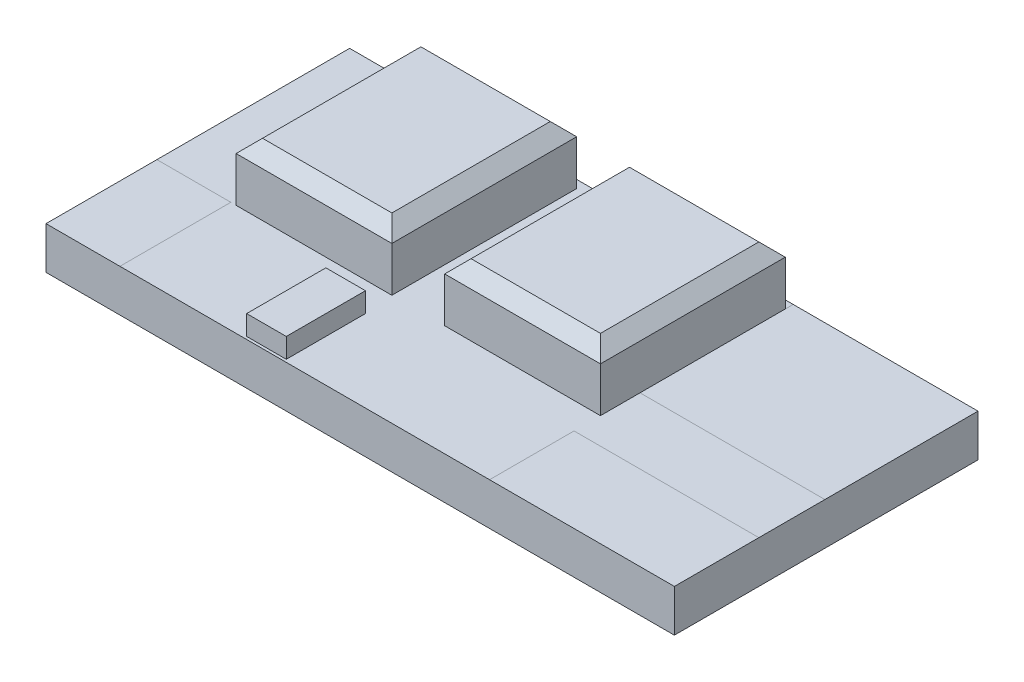
SolidWorks part; units mm, degrees
ref_plane "Alzado" through (0, 0, 0) normal (0, 0, 1) x (1, 0, 0)
ref_plane "Planta" through (0, 0, 0) normal (0, 1, 0) x (1, 0, 0)
ref_plane "Vista lateral" through (0, 0, 0) normal (1, 0, 0) x (0, 0, -1)
sketch "Croquis1" plane through (0, 0, 0) normal (0, 1, 0) x (1, 0, 0)
  line L1 (-11.9, 5.75) -> (11.9, 5.75)
  line L2 (-11.9, 5.75) -> (-11.9, -5.75)
  line L3 (-11.9, -5.75) -> (11.9, -5.75)
  line L4 (11.9, 5.75) -> (11.9, -5.75)
  line L5 (-11.9, 5.75) -> (11.9, -5.75) construction
  line L6 (-11.9, -5.75) -> (11.9, 5.75) construction
  point P0 (0, 0)
  dimension "D1" = 23.8
  dimension "D2" = 11.5
extrude "Saliente-Extruir1" add sketch "Croquis1" along normal blind 1.6
sketch "Croquis2" plane through (0, 1.6, 0) normal (0, 1, 0) x (1, 0, 0)
  line L0 (11.9, 5.75) -> (-11.9, 5.75) construction
  line L1 (-1, 5.45) -> (4.9, 5.45)
  line L2 (-1, 5.45) -> (-1, -1.55)
  line L3 (-1, -1.55) -> (4.9, -1.55)
  line L4 (4.9, 5.45) -> (4.9, -1.55)
  line L5 (-3, 5.45) -> (-8.9, 5.45)
  line L6 (-3, 5.45) -> (-3, -1.55)
  line L7 (-3, -1.55) -> (-8.9, -1.55)
  line L8 (-8.9, 5.45) -> (-8.9, -1.55)
  line L9 (-11.9, 5.75) -> (-11.9, -5.75) construction
  dimension "D1" = 5.9
  dimension "D2" = 7
  dimension "D3" = 0.3
  dimension "D4" = 2
  dimension "D5" = 3
extrude "Saliente-Extruir2" add sketch "Croquis2" along normal blind 2.2 separate body
sketch "Croquis3" plane through (0, 1.6, 0) normal (0, 1, 0) x (1, 0, 0)
  line L0 (-11.9, 5.75) -> (-11.9, -5.75) construction
  line L1 (-4.4, -2.65) -> (-2.9, -2.65)
  line L2 (-4.4, -2.65) -> (-4.4, -5.65)
  line L3 (-4.4, -5.65) -> (-2.9, -5.65)
  line L4 (-2.9, -2.65) -> (-2.9, -5.65)
  line L5 (-11.9, -5.75) -> (11.9, -5.75) construction
  dimension "D1" = 7.5
  dimension "D2" = 0.1
  dimension "D3" = 1.5
  dimension "D4" = 3
extrude "Saliente-Extruir3" add sketch "Croquis3" along normal blind 0.75 separate body
chamfer "Chaflán1" distance 0.5 angle 45 4 edges at (-5.95, 3.8, -5.45) (-3, 3.8, -1.95) (-5.95, 3.8, 1.55) (-8.9, 3.8, -1.95)
chamfer "Chaflán2" distance 0.5 angle 45 4 edges at (4.9, 3.8, -1.95) (1.95, 3.8, 1.55) (-1, 3.8, -1.95) (1.95, 3.8, -5.45)
sketch "Croquis4" plane through (0, 1.6, 0) normal (0, 1, 0) x (1, 0, 0)
  line L0 (4.9, 5.45) -> (4.9, -1.55) construction
  line L1 (11.9, 5.75) -> (4.9, 5.75)
  line L2 (11.9, 5.75) -> (11.9, -0.05)
  line L3 (11.9, -0.05) -> (4.9, -0.05)
  line L4 (4.9, 5.75) -> (4.9, -0.05)
  line L5 (4.9, -1.55) -> (-1, -1.55) construction
  line L6 (-11.9, 5.75) -> (-11.9, -5.75) construction
  line L7 (-11.9, -1.55) -> (-9.1, -1.55)
  line L8 (-11.9, -1.55) -> (-11.9, -5.75)
  line L9 (-11.9, -5.75) -> (-9.1, -5.75)
  line L10 (-9.1, -1.55) -> (-9.1, -5.75)
  line L11 (-11.9, -5.75) -> (11.9, -5.75) construction
  line L12 (-8.9, -1.55) -> (-8.9, 5.45) construction
  line L13 (-3, -1.55) -> (-8.9, -1.55) construction
  line L14 (11.9, -5.75) -> (11.9, 5.75) construction
  line L15 (4.9, -5.75) -> (11.9, -5.75)
  line L16 (4.9, -5.75) -> (4.9, -2.55)
  line L17 (4.9, -2.55) -> (11.9, -2.55)
  line L18 (11.9, -5.75) -> (11.9, -2.55)
  dimension "D1" = 1.5
  dimension "D2" = 0.2
  dimension "D3" = 1
split line "Línea de partición1"
